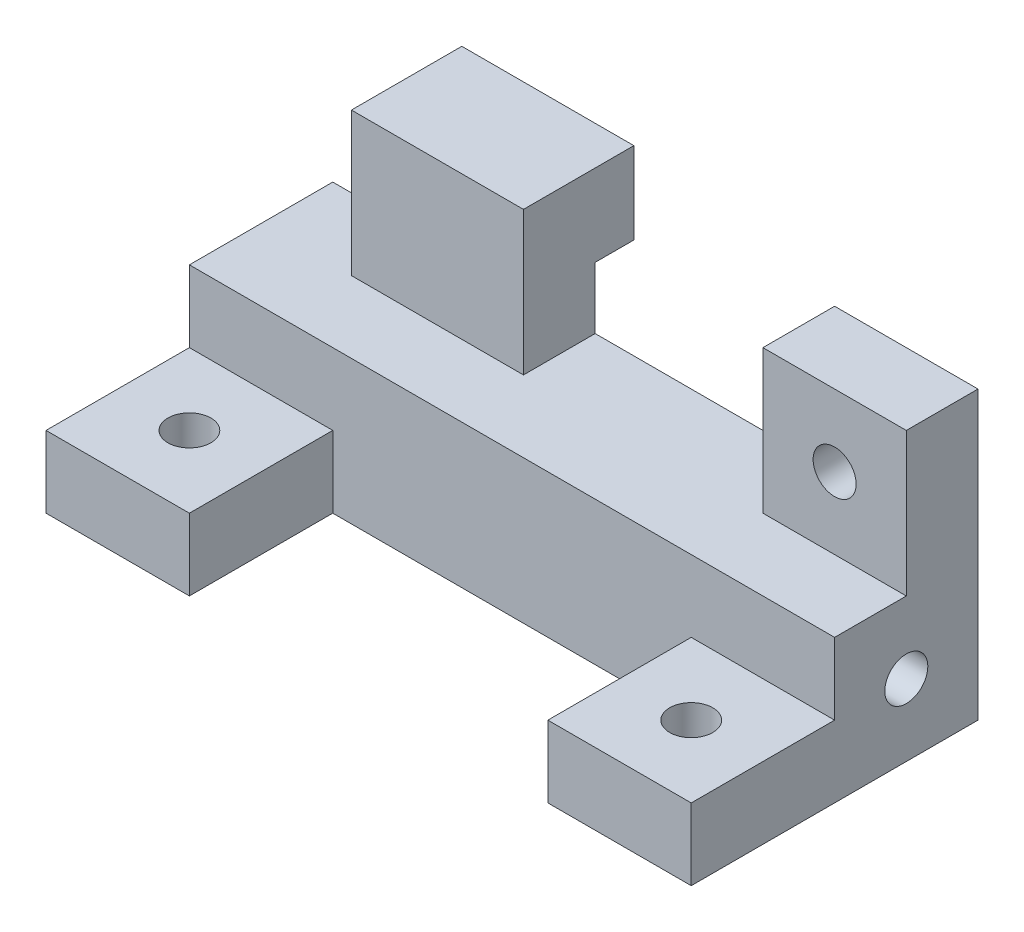
SolidWorks part; units mm, degrees
ref_plane "Front Plane" through (0, 0, 0) normal (0, 0, 1) x (1, 0, 0)
ref_plane "Top Plane" through (0, 0, 0) normal (0, 1, 0) x (1, 0, 0)
ref_plane "Right Plane" through (0, 0, 0) normal (1, 0, 0) x (0, 0, -1)
sketch "Sketch1" plane through (0, 0, 0) normal (0, 0, 1) x (1, 0, 0)
  line L1 (0, 0) -> (45, 0)
  line L2 (0, 0) -> (0, 10)
  line L3 (0, 10) -> (45, 10)
  line L4 (45, 0) -> (45, 10)
  dimension "D1" = 45
  dimension "D2" = 10
extrude "Boss-Extrude1" add sketch "Sketch1" along normal blind 10
sketch "Sketch2" plane through (0, 10, 0) normal (0, 1, 0) x (1, 0, 0)
  line L0 (45, 0) -> (0, 0) construction
  line L1 (45, 0) -> (35, 0)
  line L2 (45, 0) -> (45, -5)
  line L3 (45, -5) -> (35, -5)
  line L4 (35, 0) -> (35, -5)
  line L5 (6.3, 0) -> (18.3, 0)
  line L6 (6.3, 0) -> (6.3, -5)
  line L7 (6.3, -5) -> (18.3, -5)
  line L8 (18.3, 0) -> (18.3, -5)
  line L9 (0, -10) -> (0, 0) construction
  dimension "D1" = 5
  dimension "D2" = 10
  dimension "D3" = 5
  dimension "D4" = 6.3
  dimension "D5" = 12
extrude "Boss-Extrude2" add sketch "Sketch2" along normal blind 10
sketch "Sketch3" plane through (0, 0, 10) normal (0, 0, 1) x (1, 0, 0)
  line L1 (0, 0) -> (10, 0)
  line L2 (0, 0) -> (0, 5)
  line L3 (0, 5) -> (10, 5)
  line L4 (10, 0) -> (10, 5)
  line L5 (45, 0) -> (35, 0)
  line L6 (45, 0) -> (45, 5)
  line L7 (45, 5) -> (35, 5)
  line L8 (35, 0) -> (35, 5)
  dimension "D1" = 10
  dimension "D2" = 10
  dimension "D3" = 5
  dimension "D4" = 5
extrude "Boss-Extrude3" add sketch "Sketch3" along normal blind 10
sketch "Sketch4" plane through (0, 0, 0) normal (-1, 0, 0) x (0, 0, 1)
  line L0 (0, 10) -> (0, 0) construction
  line L1 (20, 0) -> (0, 0) construction
  circle A0 centre (5, 5) radius 1.5
  dimension "D3" = 3
  dimension "D1" = 5
  dimension "D2" = 5
extrude "Cut-Extrude1" cut sketch "Sketch4" against normal blind 5
sketch "Sketch6" plane through (0, 5, 0) normal (0, 1, 0) x (1, 0, 0)
  line L0 (10, -20) -> (10, -10) construction
  line L1 (10, -20) -> (0, -20) construction
  circle A0 centre (5, -15) radius 1.5
  dimension "D3" = 3
  dimension "D1" = 5
  dimension "D2" = 5
extrude "Cut-Extrude3" cut sketch "Sketch6" against normal blind 5
sketch "Sketch7" plane through (45, 0, 0) normal (1, 0, 0) x (0, 0, -1)
  line L0 (0, 0) -> (0, 20) construction
  line L1 (-10, 10) -> (-5, 10) construction
  circle A0 centre (-5, 5) radius 1.5
  dimension "D3" = 3
  dimension "D1" = 5
  dimension "D2" = 5
extrude "Cut-Extrude4" cut sketch "Sketch7" against normal blind 5
sketch "Sketch9" plane through (0, 5, 0) normal (0, 1, 0) x (1, 0, 0)
  line L0 (45, -20) -> (45, -10) construction
  line L1 (45, -20) -> (35, -20) construction
  circle A0 centre (40, -15) radius 1.5
  dimension "D3" = 3
  dimension "D1" = 5
  dimension "D2" = 5
extrude "Cut-Extrude6" cut sketch "Sketch9" against normal blind 5
sketch "Sketch10" plane through (0, 0, 5) normal (0, 0, 1) x (1, 0, 0)
  line L0 (35, 20) -> (35, 10) construction
  line L3 (35, 10) -> (45, 10) construction
  circle A0 centre (40, 15) radius 1.5
  point P6 (41.2345, 10)
  point P7 (31.4036, 13.9817)
  dimension "D3" = 3
  dimension "D1" = 5
  dimension "D2" = 5
extrude "Cut-Extrude7" cut sketch "Sketch10" against normal blind 5
sketch "Sketch11" plane through (0, 0, 0) normal (0, 0, -1) x (-1, 0, 0)
  line L0 (-18.3, 20) -> (-18.3, 10) construction
  line L1 (-6.3, 20) -> (-18.3, 20)
  line L2 (-6.3, 20) -> (-6.3, 14.3)
  line L3 (-6.3, 14.3) -> (-18.3, 14.3)
  line L4 (-18.3, 20) -> (-18.3, 14.3)
  line L5 (-18.3, 14.3) -> (-6.3, 14.3) construction
extrude "Boss-Extrude4" add sketch "Sketch11" along normal blind 2.7
